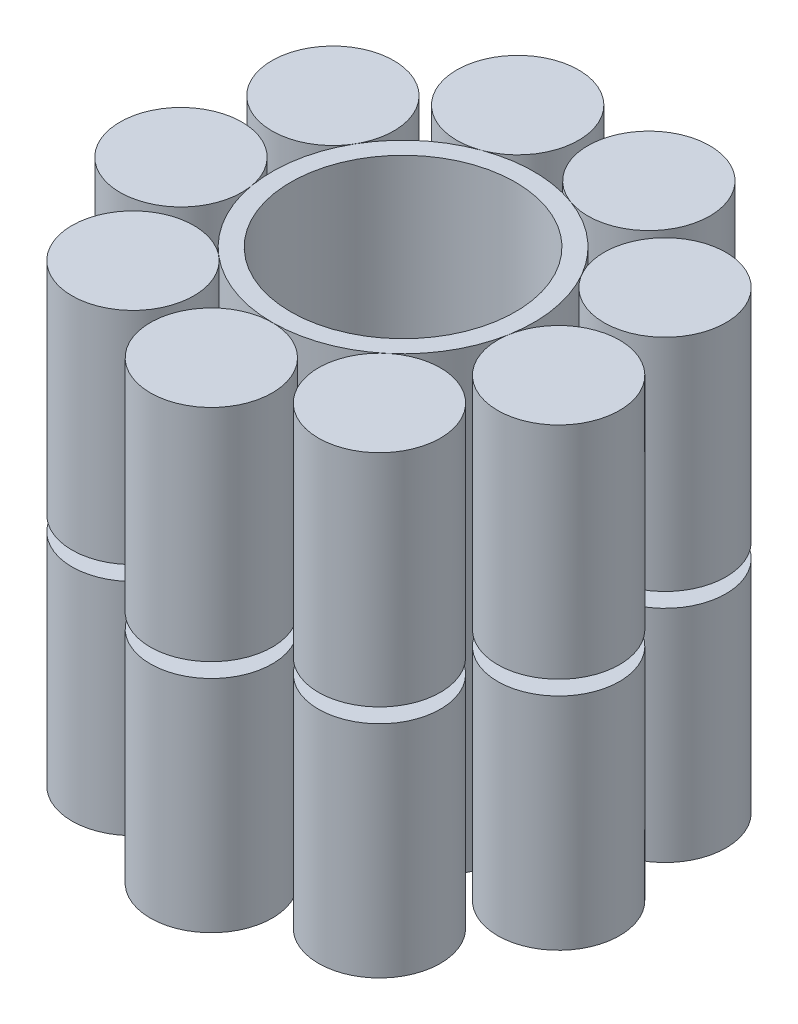
SolidWorks part; units mm, degrees
ref_plane "Front Plane" through (0, 0, 0) normal (0, 0, 1) x (1, 0, 0)
ref_plane "Top Plane" through (0, 0, 0) normal (0, 1, 0) x (1, 0, 0)
ref_plane "Right Plane" through (0, 0, 0) normal (1, 0, 0) x (0, 0, -1)
sketch "Sketch1" plane through (0, 0, 0) normal (0, 1, 0) x (1, 0, 0)
  circle A1 centre (0, 0) radius 36.5125
  circle A2 centre (0, 0) radius 31.369
  dimension "D1" = 73.025
  dimension "D2" = 62.738
extrude "Boss-Extrude1" add sketch "Sketch1" along normal blind 127
sketch "Sketch2" plane through (0, 0, 0) normal (0, 1, 0) x (1, 0, 0)
  circle A0 centre (0, -53.5305) radius 17.018
  circle A1 centre (0, 0) radius 36.5125 construction
  dimension "D2" = 34.036
extrude "Boss-Extrude2" add sketch "Sketch2" along normal blind 127 separate body
pattern_circular "CirPattern3" count 9 over 360 about axis through (0, 0, 0) along (0, 1, 0) of bodies 102
sketch "Sketch4" plane through (0, 0, 0) normal (0, 0, 1) x (1, 0, 0)
  line L0 (0, 0) -> (0, 127)
  line L1 (35.3265, 127) -> (1.2905, 127) construction
  point P5 (0, 63.5)
ref_plane "Plane1" through (0, 63.5, 0) normal (0, 1, 0) x (1, 0, 0)
sketch "Sketch5" plane through (0, 63.5, 0) normal (0, 1, 0) x (1, 0, 0)
  circle A0 centre (0, 0) radius 36.5125 construction
  circle A1 centre (0, 0) radius 36.5125
  circle A2 centre (0, 0) radius 70.5485
  circle A3 centre (0, -53.5305) radius 17.018 construction
extrude "Cut-Extrude1" cut sketch "Sketch5" against normal blind 2.032 and the other way blind 2.032
sketch "Sketch6" plane through (0, 0, 0) normal (0, 1, 0) x (1, 0, 0)
  circle A0 centre (0, 0) radius 70.5485
  circle A1 centre (46.3588, 26.7653) radius 17.018 construction
